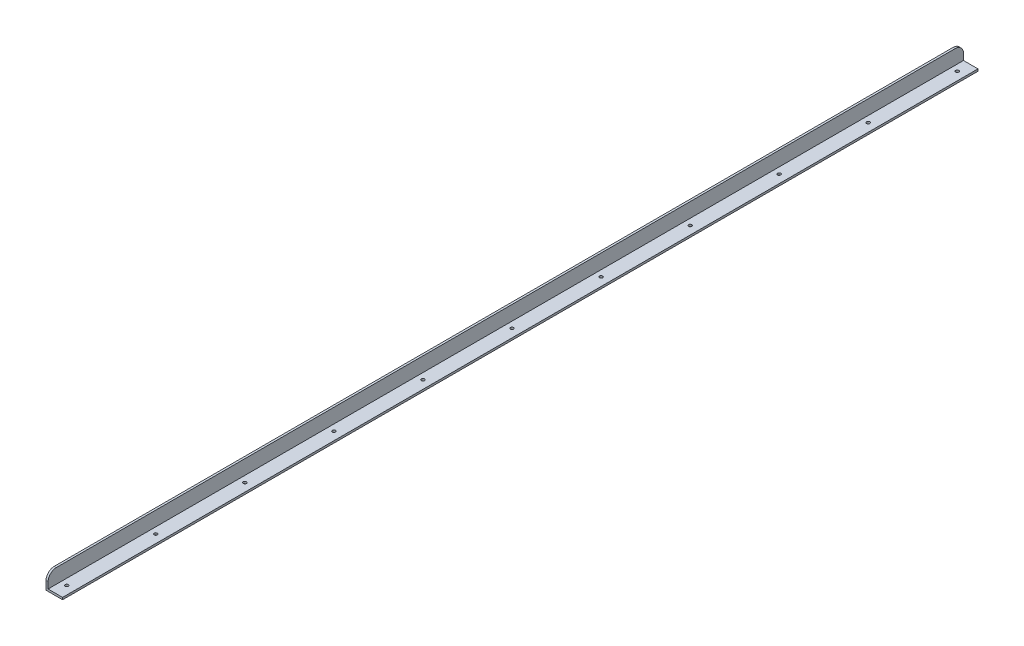
SolidWorks part; units mm, degrees
ref_plane "front" through (0, 0, 0) normal (0, 0, 1) x (1, 0, 0)
ref_plane "top" through (0, 0, 0) normal (0, 1, 0) x (1, 0, 0)
ref_plane "right" through (0, 0, 0) normal (1, 0, 0) x (0, 0, -1)
sketch "Sketch1" plane through (0, 0, 0) normal (0, 0, 1) x (1, 0, 0)
  line L0 (0, 0) -> (25.4, 0)
  line L1 (25.4, 0) -> (25.4, 3.175)
  line L2 (25.4, 3.175) -> (3.175, 3.175)
  line L3 (3.175, 3.175) -> (3.175, 25.4)
  line L4 (3.175, 25.4) -> (0, 25.4)
  line L5 (0, 25.4) -> (0, 0)
  dimension "D1" = 25.4
  dimension "D2" = 25.4
  dimension "D3" = 3.175
extrude "Extrude1" add sketch "Sketch1" against normal blind 1403.35
sketch "Sketch2" plane through (0, 0, 0) normal (0, 1, 0) x (1, 0, 0)
  circle A0 centre (12.7, 19.05) radius 2.4257
  dimension "D1" = 4.8514
  dimension "D2" = 19.05
  dimension "D3" = 12.7
extrude "Cut-Extrude2" cut sketch "Sketch2" along normal through all
pattern_linear "LPattern1" count 11 spacing 136.525 along (0, 0, -1) of "Cut-Extrude2"
fillet "Fillet1" radius 12.7 2 edges at (1.5875, 25.4, -1403.35) (1.5875, 25.4, 0)
